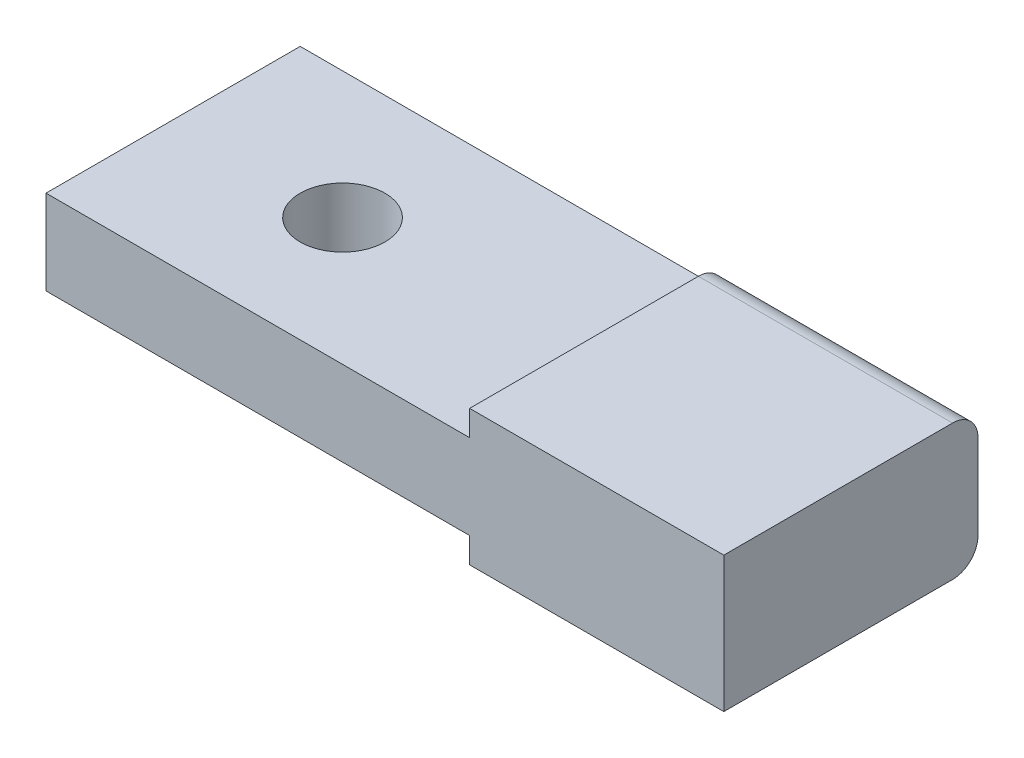
SolidWorks part; units mm, degrees
material "Copper"
ref_plane "Front Plane" through (0, 0, 0) normal (0, 0, 1) x (1, 0, 0)
ref_plane "Top Plane" through (0, 0, 0) normal (0, 1, 0) x (1, 0, 0)
ref_plane "Right Plane" through (0, 0, 0) normal (1, 0, 0) x (0, 0, -1)
sketch "Sketch1" plane through (0, 0, 0) normal (0, 0, 1) x (1, 0, 0)
  line L1 (0, 0) -> (40, 0)
  line L2 (0, 0) -> (0, 8)
  line L3 (0, 8) -> (40, 8)
  line L4 (40, 0) -> (40, 8)
  dimension "D1" = 8
  dimension "D2" = 40
extrude "Boss-Extrude1" add sketch "Sketch1" along normal blind 15
sketch "Sketch2" plane through (0, 0, 15) normal (0, 0, 1) x (1, 0, 0)
  line L1 (-4.0346, 18.4172) -> (25, 18.4172)
  line L2 (-4.0346, 18.4172) -> (-4.0346, 6.5)
  line L3 (-4.0346, 6.5) -> (25, 6.5)
  line L4 (25, 18.4172) -> (25, 6.5)
  line L5 (0, -4.4) -> (0, 4.4) construction
  line L7 (-5.5895, 1.5) -> (25, 1.5)
  line L8 (-5.5895, 1.5) -> (-5.5895, -6.4483)
  line L9 (-5.5895, -6.4483) -> (25, -6.4483)
  line L10 (25, 1.5) -> (25, -6.4483)
  line L11 (-3.6238, 4) -> (50.8894, 4) construction
  line L12 (40, 8) -> (0, 8) construction
  dimension "D1" = 4
  dimension "D2" = 25
  dimension "D3" = 5
  dimension "D4" = 1.5
extrude "Cut-Extrude1" cut sketch "Sketch2" against normal blind 15
sketch "Sketch3" plane through (0, 6.5, 0) normal (0, 1, 0) x (1, 0, 0)
  line L0 (-4.4, 0) -> (4.4, 0) construction
  line L1 (0, -4.4) -> (0, 4.4) construction
  circle A0 centre (10, -7.5) radius 2.5
  dimension "D1" = 5
  dimension "D2" = 7.5
  dimension "D3" = 10
extrude "Cut-Extrude2" cut sketch "Sketch3" against normal blind 15 contours A0
ref_plane "Plane1" through (0, 3, 0) normal (0, 1, 0) x (1, 0, 0)
fillet "Fillet1" radius 1.5 2 edges at (32.5, 8, 0) (32.5, 0, 0)
